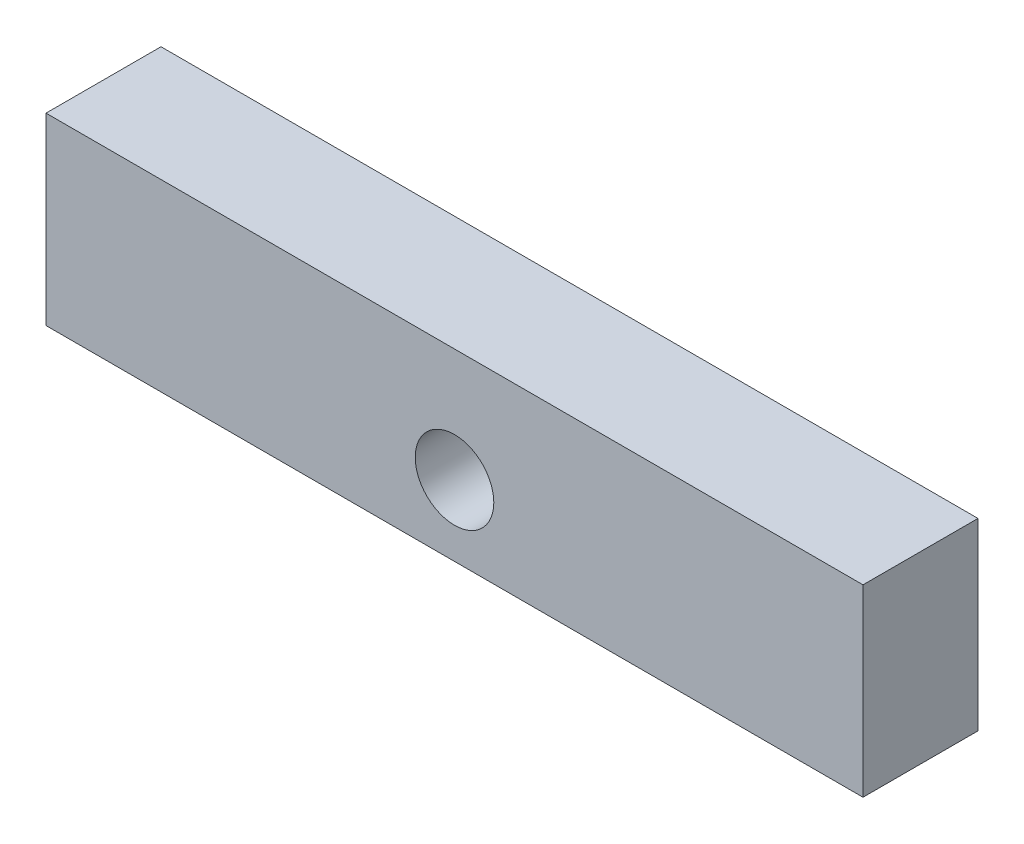
SolidWorks part; units mm, degrees
material "Листовая углеродистая сталь 1023 (SS)"
ref_plane "Спереди" through (0, 0, 0) normal (0, 0, 1) x (1, 0, 0)
ref_plane "Сверху" through (0, 0, 0) normal (0, 1, 0) x (1, 0, 0)
ref_plane "Справа" through (0, 0, 0) normal (1, 0, 0) x (0, 0, -1)
sketch "Эскиз1" plane through (0, 0, 0) normal (0, 0, 1) x (1, 0, 0)
  line L1 (-63.9775, 32.838) -> (42.5925, 32.838)
  line L2 (-63.9775, 32.838) -> (-63.9775, 8.838)
  line L3 (-63.9775, 8.838) -> (42.5925, 8.838)
  line L4 (42.5925, 32.838) -> (42.5925, 8.838)
  dimension "D1" = 106.57
  dimension "D2" = 24
extrude "Бобышка-Вытянуть1" add sketch "Эскиз1" along normal blind 15
sketch "Эскиз2" plane through (0, 0, 15) normal (0, 0, 1) x (1, 0, 0)
  line L0 (-10.6925, 32.838) -> (-10.6925, 8.838) construction
  line L1 (42.5925, 32.838) -> (-63.9775, 32.838) construction
  line L2 (-63.9775, 8.838) -> (42.5925, 8.838) construction
  circle A0 centre (-10.6925, 18.0493) radius 5.125
  dimension "D1" = 10.25
extrude "Вырез-Вытянуть1" cut sketch "Эскиз2" against normal blind 15
cosmetic thread "Условное изображение резьбы1" parameters "D2"=12
